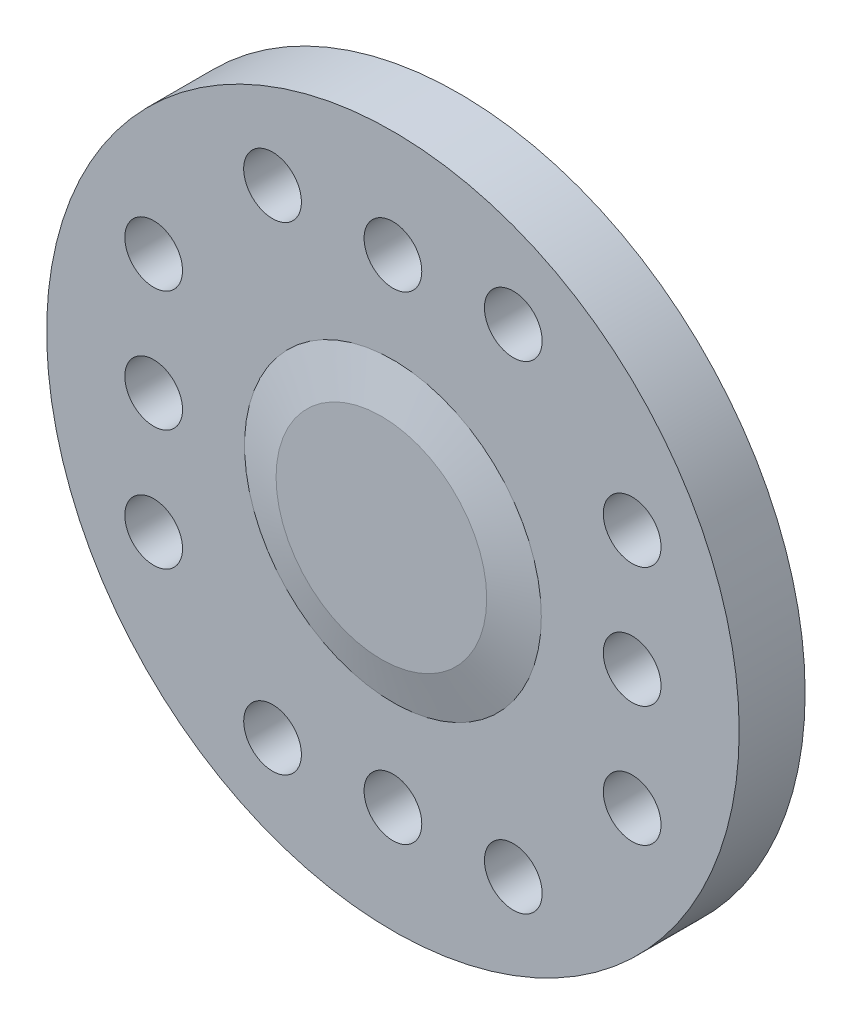
SolidWorks part; units mm, degrees
ref_plane "Plan de face" through (0, 0, 0) normal (0, 0, 1) x (1, 0, 0)
ref_plane "Plan de dessus" through (0, 0, 0) normal (0, 1, 0) x (1, 0, 0)
ref_plane "Plan de droite" through (0, 0, 0) normal (1, 0, 0) x (0, 0, -1)
sketch "Esquisse1" plane through (0, 0, 0) normal (0, 0, 1) x (1, 0, 0)
  line L0 (0, 0) -> (58.9528, 0) construction
  line L1 (7.2545, 0) -> (7.2545, 12.5737) construction
  circle A0 centre (0, 0) radius 10.5
  circle A1 centre (7.2545, 3.65) radius 0.875
  circle A2 centre (7.2545, 0) radius 0.875
  circle A3 centre (7.2545, -3.65) radius 0.875
  circle A4 centre (3.65, -7.2545) radius 0.875
  circle A5 centre (0, -7.2545) radius 0.875
  circle A6 centre (-3.65, -7.2545) radius 0.875
  circle A7 centre (-7.2545, -3.65) radius 0.875
  circle A8 centre (-7.2545, 0) radius 0.875
  circle A9 centre (-7.2545, 3.65) radius 0.875
  circle A10 centre (-3.65, 7.2545) radius 0.875
  circle A11 centre (0, 7.2545) radius 0.875
  circle A12 centre (3.65, 7.2545) radius 0.875
  point P31 (0, 0)
  dimension "D1" = 1.75
  dimension "D2" = 21
  dimension "D4" = 1.75
  dimension "D3" = 7.2545
  dimension "D5" = 3.65
  dimension "D7" = 4
extrude "Boss.-Extru.1" add sketch "Esquisse1" along normal blind 2
sketch "Esquisse2" plane through (0, 0, 2) normal (0, 0, 1) x (1, 0, 0)
  circle A0 centre (0, 0) radius 4.5
  dimension "D1" = 9
extrude "Boss.-Extru.2" add sketch "Esquisse2" along normal blind 0.35 draft 75
sketch "Esquisse3" plane through (0, 0, 0) normal (0, 0, -1) x (-1, 0, 0)
  circle A0 centre (0, 0) radius 4
  dimension "D1" = 8
extrude "Boss.-Extru.3" add sketch "Esquisse3" along normal blind 3.4
sketch "Esquisse4" plane through (0, 0, -3.4) normal (0, 0, -1) x (-1, 0, 0)
  circle A0 centre (0, 0) radius 2.85
  dimension "D1" = 5.7
extrude "Enlèv. mat.-Extru.1" cut sketch "Esquisse4" against normal blind 3.8
